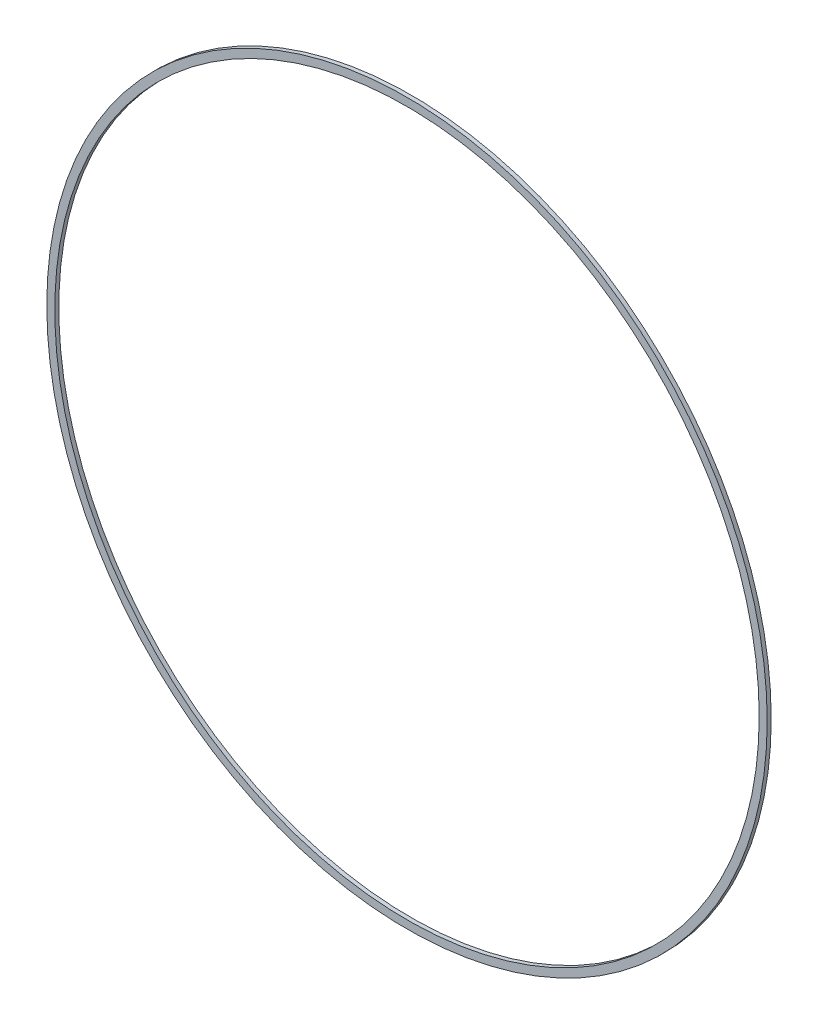
SolidWorks part; units mm, degrees
ref_plane "前视基准面" through (0, 0, 0) normal (0, 0, 1) x (1, 0, 0)
ref_plane "上视基准面" through (0, 0, 0) normal (0, 1, 0) x (1, 0, 0)
ref_plane "右视基准面" through (0, 0, 0) normal (1, 0, 0) x (0, 0, -1)
sketch "草图1" plane through (0, 0, 0) normal (0, 0, 1) x (1, 0, 0)
  circle A0 centre (0, 0) radius 90
  circle A1 centre (0, 0) radius 88
  dimension "D1" = 180
  dimension "D2" = 2
extrude "凸台-拉伸1" add sketch "草图1" along normal blind 1
